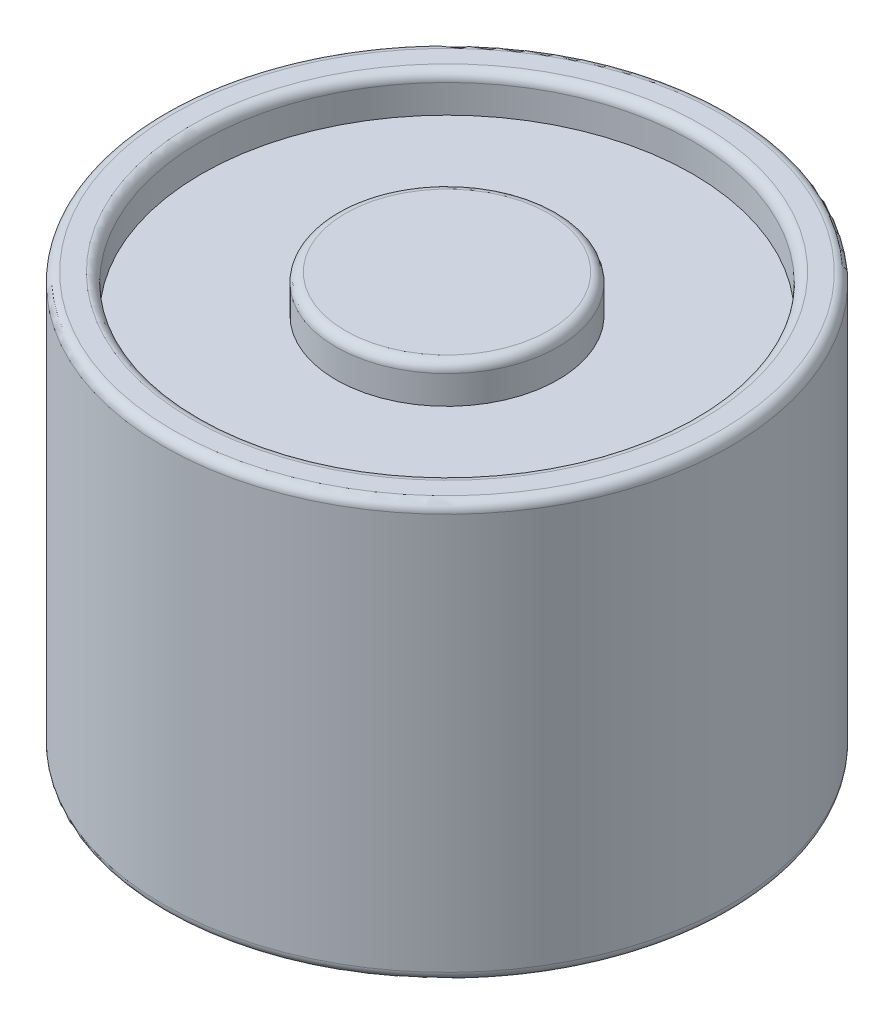
SolidWorks part; units mm, degrees
ref_plane "Front Plane" through (0, 0, 0) normal (0, 0, 1) x (1, 0, 0)
ref_plane "Top Plane" through (0, 0, 0) normal (0, 1, 0) x (1, 0, 0)
ref_plane "Right Plane" through (0, 0, 0) normal (1, 0, 0) x (0, 0, -1)
sketch "Sketch1" plane through (0, 0, 0) normal (0, 1, 0) x (1, 0, 0)
  circle A0 centre (0, 0) radius 15
  dimension "D1" = 30
extrude "Boss-Extrude1" add sketch "Sketch1" along normal blind 22
sketch "Sketch2" plane through (0, 22, 0) normal (0, 1, 0) x (1, 0, 0)
  circle A0 centre (0, 0) radius 13
  circle A1 centre (0, 0) radius 5.8803
  dimension "D1" = 26
extrude "Cut-Extrude1" cut sketch "Sketch2" against normal blind 2
fillet "Fillet1" radius 0.5 4 edges at (0, 22, 5.8803) (0, 0, 15) (0, 22, 13) (0, 22, 15)
